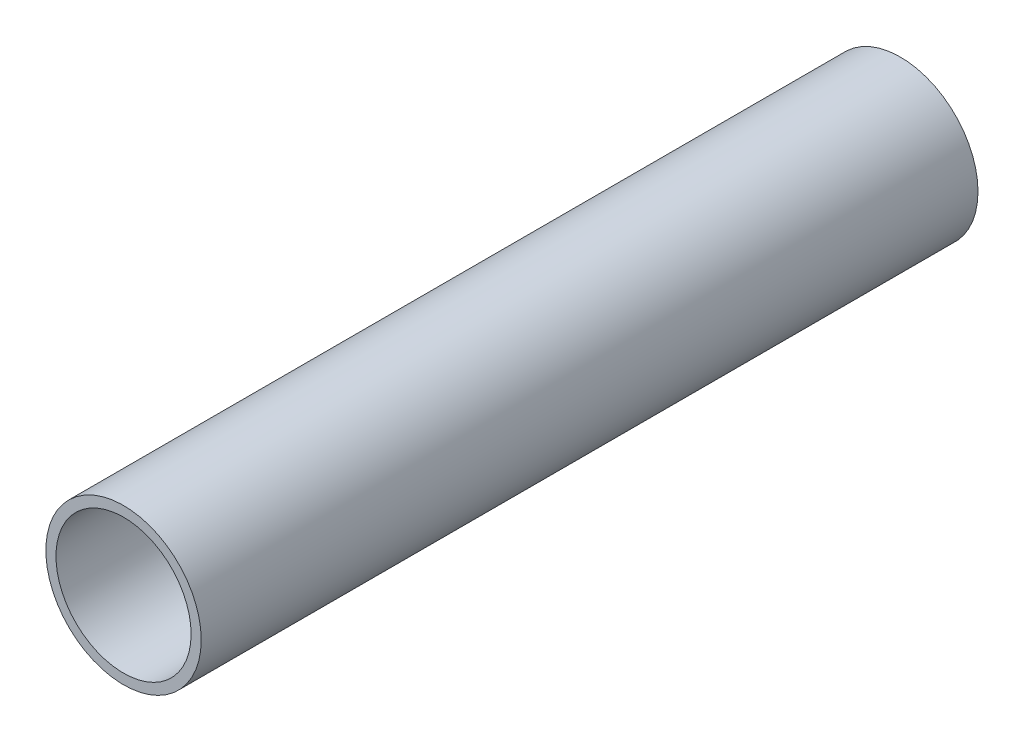
SolidWorks part; units mm, degrees
ref_plane "Front Plane" through (0, 0, 0) normal (0, 0, 1) x (1, 0, 0)
ref_plane "Top Plane" through (0, 0, 0) normal (0, 1, 0) x (1, 0, 0)
ref_plane "Right Plane" through (0, 0, 0) normal (1, 0, 0) x (0, 0, -1)
sketch "Sketch1" plane through (0, 0, 0) normal (0, 0, 1) x (1, 0, 0)
  line L0 (12.7, 0) -> (11.049, 0) construction
  line L1 (-12.7, 0) -> (12.7, 0) construction
  dimension "OD" = 25.4
  dimension "Wall Thickness" = 1.651
sketch "Sketch2" plane through (0, 0, 0) normal (1, 0, 0) x (0, 0, -1)
  line L0 (76.2, 0) -> (-76.2, 0)
  point P4 (0, 0)
  dimension "Length" = 152.4
sketch "Sketch3" plane through (0, 0, 0) normal (0, 0, 1) x (1, 0, 0)
  circle A0 centre (0, 0) radius 12.7
  circle A1 centre (0, 0) radius 11.049
extrude "Boss-Extrude1" add sketch "Sketch3" along normal blind 50.8 and the other way up to vertex (76.2 mm away) other way up to point (0, 0, -76.2)
